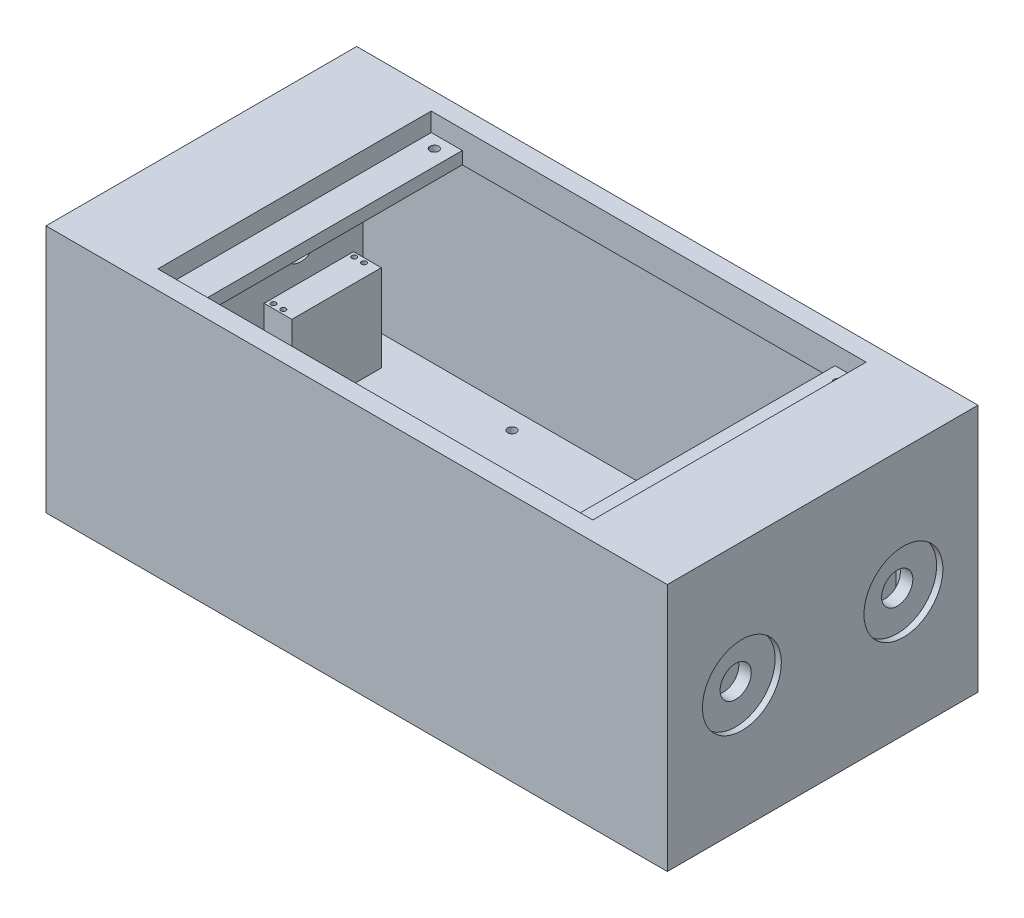
SolidWorks part; units mm, degrees
other "Markup1"
sketch "Sketch8" plane through (250, -50, -125) normal (1, 0, 0) x (0, 0, -1)
ref_plane "Front Plane" through (0, 0, 0) normal (0, 0, 1) x (1, 0, 0)
ref_plane "Top Plane" through (0, 0, 0) normal (0, 1, 0) x (1, 0, 0)
ref_plane "Right Plane" through (0, 0, 0) normal (1, 0, 0) x (0, 0, -1)
sketch "Sketch1" plane through (0, 0, 0) normal (1, 0, 0) x (0, 0, -1)
  line L1 (-125, -100) -> (125, -100)
  line L2 (-125, -100) -> (-125, 100)
  line L3 (-125, 100) -> (125, 100)
  line L4 (125, -100) -> (125, 100)
  line L5 (-125, -100) -> (125, 100) construction
  line L6 (-125, 100) -> (125, -100) construction
  point P0 (0, 0)
  dimension "D1" = 250
  dimension "D2" = 200
extrude "Boss-Extrude1" add sketch "Sketch1" along normal mid plane 500
sketch "Sketch7" plane through (0, 0, 0) normal (0, 1, 0) x (1, 0, 0)
  line L1 (-235, -115) -> (235, -115)
  line L2 (-235, -115) -> (-235, 115)
  line L3 (-235, 115) -> (235, 115)
  line L4 (235, -115) -> (235, 115)
  line L5 (-235, -115) -> (235, 115) construction
  line L6 (-235, 115) -> (235, -115) construction
  point P0 (0, 0)
  dimension "D1" = 470
  dimension "D2" = 230
extrude "Cut-Extrude4" cut sketch "Sketch7" against normal mid plane 160
sketch "Sketch5" plane through (250, 0, 0) normal (1, 0, 0) x (0, 0, -1)
  line L0 (-125, 100) -> (-125, -100) construction
  circle A0 centre (-65, 0) radius 31.75
  dimension "D1" = 63.5
  dimension "D2" = 60
extrude "63.5mm_dia_servo" cut sketch "Sketch5" against normal blind 5
mirror "Mirror12" about plane through (0, 0, 0) normal (0, 0, 1) of "63.5mm_dia_servo"
mirror "Mirror13" about plane through (0, 0, 0) normal (1, 0, 0) of "Mirror12", "63.5mm_dia_servo"
sketch "Sketch10" plane through (0, 100, 0) normal (0, 1, 0) x (1, 0, 0)
  line L1 (-175, -110) -> (175, -110)
  line L2 (-175, -110) -> (-175, 110)
  line L3 (-175, 110) -> (175, 110)
  line L4 (175, -110) -> (175, 110)
  line L5 (-175, -110) -> (175, 110) construction
  line L6 (-175, 110) -> (175, -110) construction
  point P0 (0, 0)
  dimension "D1" = 350
  dimension "D2" = 220
extrude "Cut-Extrude5" cut sketch "Sketch10" against normal blind 20
ref_plane "Plane4" through (0, 75, 0) normal (0, 1, 0) x (1, 0, 0)
sketch "Sketch15" plane through (0, 75, 0) normal (0, 1, 0) x (1, 0, 0)
  line L1 (-250, -125) -> (250, -125)
  line L2 (-250, -125) -> (-250, 125)
  line L3 (-250, 125) -> (250, 125)
  line L4 (250, -125) -> (250, 125)
  line L5 (-250, -125) -> (250, 125) construction
  line L6 (-250, 125) -> (250, -125) construction
  point P0 (0, 0)
extrude "Boss-Extrude2" add sketch "Sketch15" along normal blind 10
sketch "Sketch18" plane through (0, 85, 0) normal (0, 1, 0) x (1, 0, 0)
  line L0 (175, 110) -> (-175, 110) construction
  line L1 (-150, -110) -> (150, -110)
  line L2 (-150, -110) -> (-150, 110)
  line L3 (-150, 110) -> (150, 110)
  line L4 (150, -110) -> (150, 110)
  line L5 (-150, -110) -> (150, 110) construction
  line L6 (-150, 110) -> (150, -110) construction
  point P0 (0, 0)
  dimension "D1" = 300
extrude "Cut-Extrude11" cut sketch "Sketch18" against normal blind 10
sketch "Sketch19" plane through (0, 85, 0) normal (0, 1, 0) x (1, 0, 0)
  line L0 (175, 110) -> (-175, 110) construction
  circle A0 centre (-162.5, 100) radius 3.5
  dimension "D2" = 7
  dimension "D1" = 162.5
  dimension "D3" = 10
extrude "Cut-Extrude12" cut sketch "Sketch19" against normal blind 10
mirror "Mirror14" about plane through (0, 0, 0) normal (0, 0, 1) of "Cut-Extrude12"
mirror "Mirror15" about plane through (0, 0, 0) normal (1, 0, 0) of "Mirror14", "Cut-Extrude12"
sketch "Sketch20" plane through (0, -80, 0) normal (0, 1, 0) x (1, 0, 0)
  line L0 (175, 110) -> (-175, 110) construction
  circle A0 centre (-100, 100) radius 3.5
  dimension "D1" = 7
  dimension "D2" = 100
  dimension "D3" = 10
extrude "Cut-Extrude13" cut sketch "Sketch20" against normal blind 10
mirror "Mirror16" about plane through (0, 0, 0) normal (0, 0, 1) of "Cut-Extrude13"
mirror "Mirror17" about plane through (0, 0, 0) normal (1, 0, 0) of "Mirror16", "Cut-Extrude13"
sketch "Sketch22" plane through (245, 0, 0) normal (1, 0, 0) x (0, 0, -1)
  circle A0 centre (-65, 0) radius 12.55
extrude "Cut-Extrude14" cut sketch "Sketch22" against normal blind 10
mirror "Mirror18" about plane through (0, 0, 0) normal (1, 0, 0) of "Cut-Extrude14"
mirror "Mirror19" about plane through (0, 0, 0) normal (0, 0, 1) of "Mirror18", "Cut-Extrude14"
sketch "Sketch23" plane through (0, -80, 0) normal (0, 1, 0) x (1, 0, 0)
  line L0 (235, 77.55) -> (235, 52.45) construction
  line L1 (196, 90.85) -> (218.35, 90.85)
  line L2 (196, 90.85) -> (196, 18.85)
  line L3 (196, 18.85) -> (218.35, 18.85)
  line L4 (218.35, 90.85) -> (218.35, 18.85)
  line L5 (235, 115) -> (-235, 115) construction
  line L6 (235, -115) -> (235, 115) construction
  point P4 (219.3784, 6.3364)
  dimension "D1" = 16.65
  dimension "D2" = 24.15
  dimension "D3" = 39
extrude "Boss-Extrude3" add sketch "Sketch23" along normal blind 69.9
ref_plane "Plane7" through (196, -10.1, -90.85) normal (0, 0, 1) x (1, 0, 0)
mirror "Mirror20" about plane through (0, 0, 0) normal (1, 0, 0) of "Boss-Extrude3"
mirror "Mirror21" about plane through (0, 0, 0) normal (0, 0, 1) of "Mirror20", "Boss-Extrude3"
sketch "Sketch27" plane through (0, -10.1, 0) normal (0, 1, 0) x (1, 0, 0)
  line L0 (-218.35, 18.85) -> (-218.35, 90.85) construction
  line L1 (-196, 18.85) -> (-218.35, 18.85) construction
  line L2 (-214.35, 22.35) -> (-199.7043, 22.35) construction
  line L3 (-214.35, 87.35) -> (-206.35, 87.35) construction
  line L4 (-218.35, 90.85) -> (-196, 90.85) construction
  line L6 (-218.35, 18.85) -> (-218.35, 90.85) construction
  circle A0 centre (-214.35, 22.35) radius 2
  circle A1 centre (-206.35, 22.35) radius 2
  circle A2 centre (-214.35, 87.35) radius 2
  circle A3 centre (-206.35, 87.35) radius 2
  point P17 (-218.35, 87.9972)
  dimension "D2" = 12
  dimension "D4" = 3.5
  dimension "D1" = 4
  dimension "D3" = 3.5
  dimension "D5" = 4
  dimension "D6" = 12
hole_wizard "Ø1.0mm Dowel Hole1" positions "Sketch28" profile "Sketch29" hole size "Ø1.0" standard "ANSI Metric"
sketch "Sketch28" plane through (0, -10.1, 0) normal (0, 1, 0) x (1, 0, 0)
  point P0 (-214.35, 87.35)
  point P3 (-206.35, 87.35)
  point P6 (-206.35, 22.35)
  point P9 (-214.35, 22.35)
sketch "Sketch29" plane through (-214.35, -10.1, -87.35) normal (1, 0, 0) x (0, 0, 1)
  line L0 (0, 0) -> (0, 9.2017)
  line L1 (0, 9.2017) -> (2, 8)
  line L2 (2, 8) -> (2, 0)
  line L5 (2, 0) -> (0, 0)
  line L10 (0, 9.2017) -> (-2, 8) construction
  line L11 (0, -6.35) -> (0, 107.95) construction
  dimension "Hole Dia." = 4
  dimension "Hole Depth" = 8
  dimension "Drill Angle" = 118
mirror "Mirror22" about plane through (0, 0, 0) normal (0, 0, 1) of "Ø1.0mm Dowel Hole1"
mirror "Mirror23" about plane through (0, 0, 0) normal (1, 0, 0) of "Mirror22", "Ø1.0mm Dowel Hole1"
